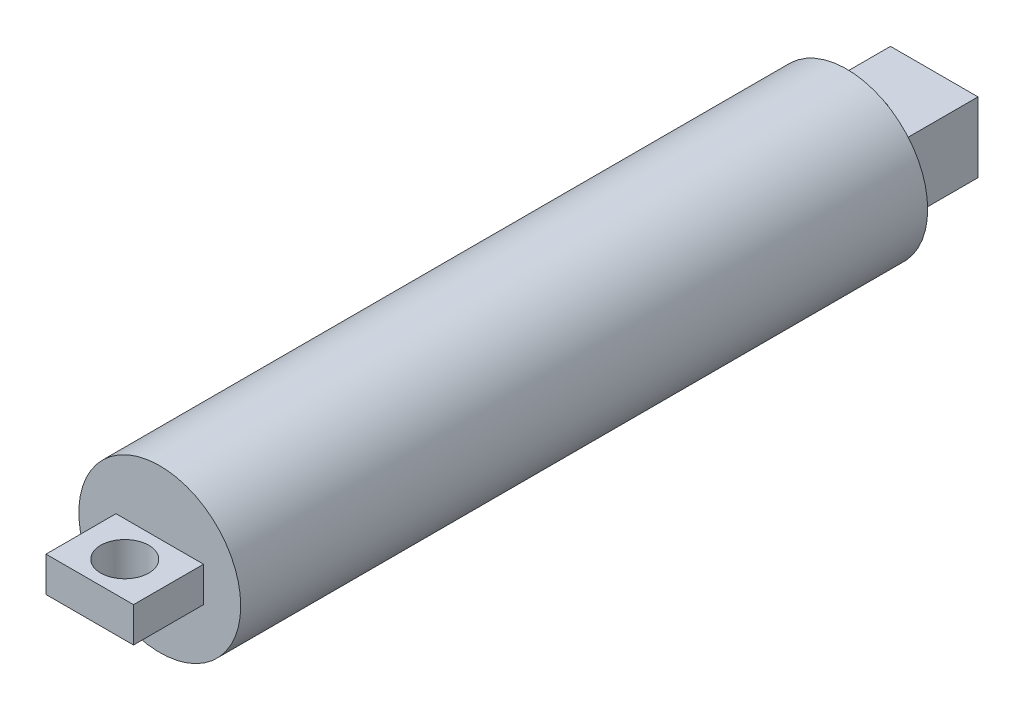
SolidWorks part; units mm, degrees
ref_plane "前视基准面" through (0, 0, 0) normal (0, 0, 1) x (1, 0, 0)
ref_plane "上视基准面" through (0, 0, 0) normal (0, 1, 0) x (1, 0, 0)
ref_plane "右视基准面" through (0, 0, 0) normal (1, 0, 0) x (0, 0, -1)
other "Configuration Table"
sketch "草图1" plane through (0, 0, 0) normal (0, 0, 1) x (1, 0, 0)
  circle A0 centre (0, 0) radius 9.25
  dimension "D1" = 18.5
extrude "凸台-拉伸1" add sketch "草图1" along normal blind 78.5
sketch "草图2" plane through (0, 0, 0) normal (0, 0, -1) x (-1, 0, 0)
  line L2 (5, -4) -> (-5, -4)
  line L3 (5, -4) -> (5, 4)
  line L4 (5, 4) -> (-5, 4)
  line L5 (-5, -4) -> (-5, 4)
  line L6 (5, -4) -> (-5, 4) construction
  line L7 (5, 4) -> (-5, -4) construction
  point P1 (0, 0)
  dimension "D1" = 10
  dimension "D2" = 8
extrude "凸台-拉伸2" add sketch "草图2" along normal blind 10
sketch "草图3" plane through (0, 0, 78.5) normal (0, 0, 1) x (1, 0, 0)
  line L1 (5, -2) -> (-5, -2)
  line L2 (5, -2) -> (5, 2)
  line L3 (5, 2) -> (-5, 2)
  line L4 (-5, -2) -> (-5, 2)
  line L5 (5, -2) -> (-5, 2) construction
  line L6 (5, 2) -> (-5, -2) construction
  point P0 (0, 0)
  dimension "D1" = 10
  dimension "D2" = 4
extrude "凸台-拉伸3" add sketch "草图3" along normal blind 8
sketch "草图5" plane through (0, 4, 0) normal (0, 1, 0) x (1, 0, 0)
  line L0 (5, -86.5) -> (-5, -86.5) construction
  line L1 (0, -82.5) -> (0, -86.5) construction
  circle A0 centre (0, 2.5) radius 1.65
  circle A1 centre (0, -82.5) radius 2.75
  dimension "D1" = 3.3
  dimension "D2" = 5.5
  dimension "D3" = 4
  dimension "D4" = 85
extrude "切除-拉伸1" cut sketch "草图5" against normal through all and the other way through all contours A1 | A0
